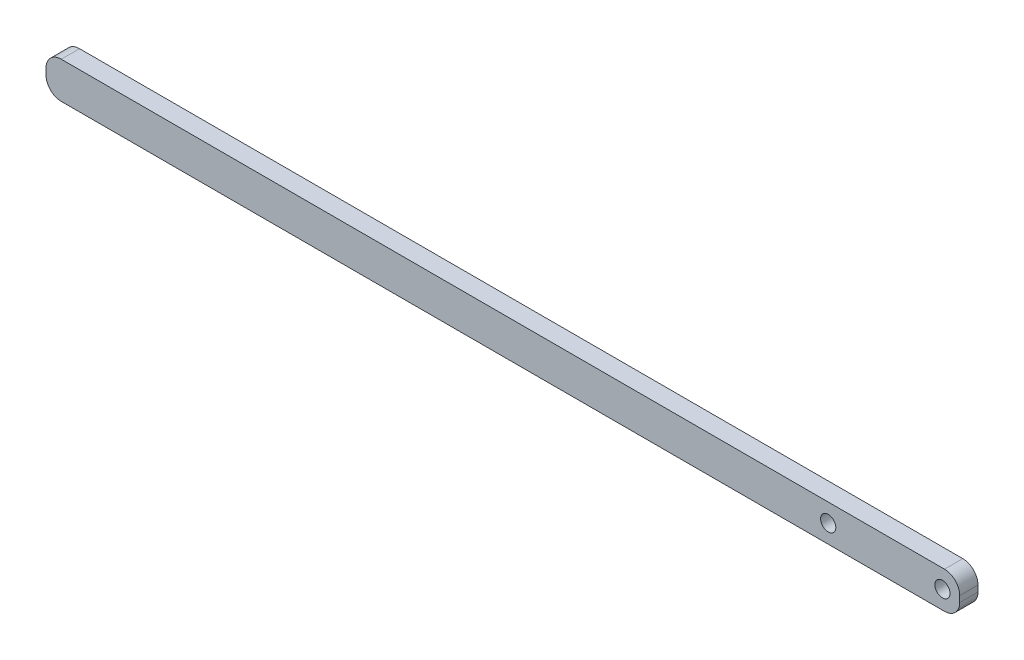
SolidWorks part; units mm, degrees
material "1060 Alloy"
ref_plane "Front Plane" through (0, 0, 0) normal (0, 0, 1) x (1, 0, 0)
ref_plane "Top Plane" through (0, 0, 0) normal (0, 1, 0) x (1, 0, 0)
ref_plane "Right Plane" through (0, 0, 0) normal (1, 0, 0) x (0, 0, -1)
sketch "Sketch1" plane through (0, 0, 0) normal (0, 0, 1) x (1, 0, 0)
  line L1 (-150, 6) -> (150, 6)
  line L2 (-150, 6) -> (-150, -6)
  line L3 (-150, -6) -> (150, -6)
  line L4 (150, 6) -> (150, -6)
  line L5 (-150, 6) -> (150, -6) construction
  line L6 (-150, -6) -> (150, 6) construction
  point P0 (0, 0)
  dimension "D1" = 12
  dimension "D2" = 300
extrude "Boss-Extrude1" add sketch "Sketch1" along normal blind 6
fillet "Fillet1" radius 5 4 edges at (-150, -6, 3) (150, -6, 3) (150, 6, 3) (-150, 6, 3)
sketch "Sketch2" plane through (0, 0, 0) normal (0, 0, -1) x (-1, 0, 0)
  line L0 (-145, 6) -> (145, 6) construction
  line L1 (145, -6) -> (-145, -6) construction
  line L2 (-150, -1) -> (-150, 1) construction
  circle A0 centre (-144.3226, 0) radius 2.5
  circle A1 centre (-106.8226, 0) radius 2.5
  point P8 (0, 0)
  dimension "D1" = 5
  dimension "D2" = 5
  dimension "D3" = 6
  dimension "D4" = 6
  dimension "D5" = 37.5
  dimension "D6" = 5.6774
extrude "Cut-Extrude1" cut sketch "Sketch2" against normal blind 6
chamfer "Chamfer2" distance 1 angle 45 1 edges at (141.8226, 0, 0)
